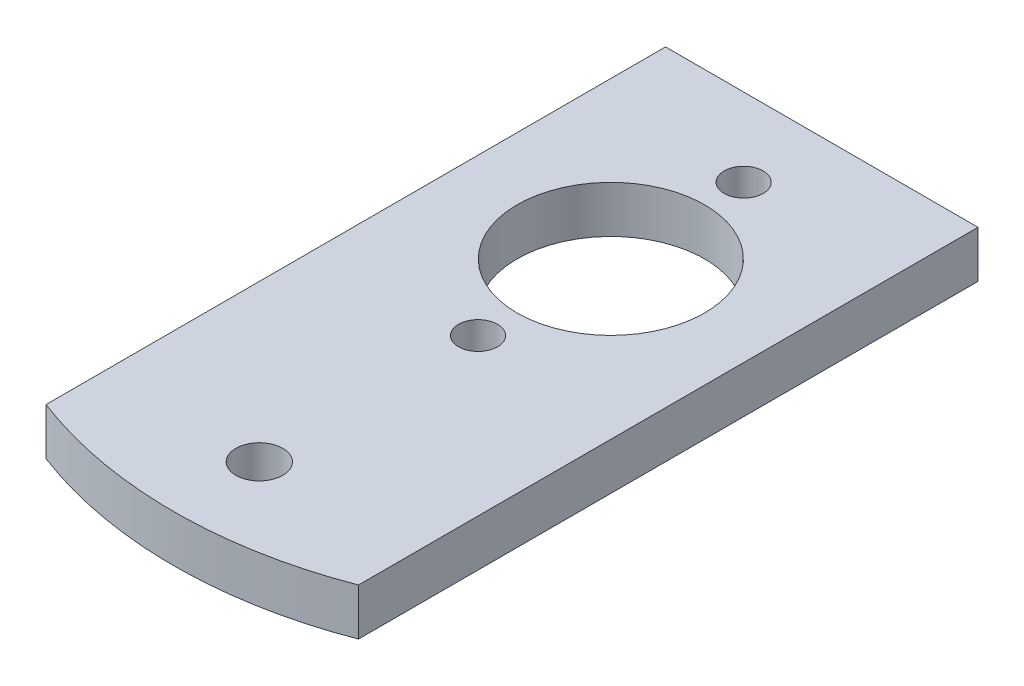
SolidWorks part; units mm, degrees
ref_plane "Front Plane" through (0, 0, 0) normal (0, 0, 1) x (1, 0, 0)
ref_plane "Top Plane" through (0, 0, 0) normal (0, 1, 0) x (1, 0, 0)
ref_plane "Right Plane" through (0, 0, 0) normal (1, 0, 0) x (0, 0, -1)
sketch "Sketch1" plane through (0, 0, 0) normal (0, 1, 0) x (1, 0, 0)
  line L0 (0, 0) -> (0, 1) construction
  line L1 (-10, -23) -> (10, -23)
  line L2 (-10, -23) -> (-10, 23)
  line L3 (-10, 23) -> (10, 23)
  line L4 (10, -23) -> (10, 23)
  line L5 (-10, -23) -> (10, 23) construction
  line L6 (-10, 23) -> (10, -23) construction
  line L7 (0, 1) -> (0, 18) construction
  line L8 (0, 9.5) -> (6, 9.5) construction
  line L9 (0, 0) -> (0, -13) construction
  circle A1 centre (0, 18) radius 1.25
  circle A2 centre (0, 9.5) radius 6
  circle A3 centre (0, 1) radius 1.25
  circle A4 centre (0, -13) radius 1.5
  point P2 (0, 0)
  dimension "D1" = 2.5
  dimension "D4" = 12
  dimension "D5" = 17
  dimension "D7" = 3
  dimension "D8" = 22.5
  dimension "D2" = 20
  dimension "D3" = 46
  dimension "D6" = 1
extrude "Boss-Extrude1" add sketch "Sketch1" along normal blind 3
sketch "Sketch2" plane through (0, 3, 0) normal (0, 1, 0) x (1, 0, 0)
  line L0 (-10, -16.6534) -> (-10, -36.6534)
  line L1 (-10, 23) -> (-10, -23) construction
  line L2 (-10, -36.6534) -> (10, -36.6534)
  line L3 (10, -36.6534) -> (10, -16.6534)
  line L4 (10, -23) -> (10, 23) construction
  circle A0 centre (0, 9.5) radius 28
  line M2 (10, -23) -> (10, 23)
  line M4 (-10, 23) -> (-10, -23)
  line M5 (-10, -23) -> (10, -23)
  dimension "D1" = 56
  dimension "D2" = 20
extrude "Cut-Extrude1" cut sketch "Sketch2" against normal through all both and the other way through all contours L2 L3 L0 M5 | A0 M4 M5 M2
